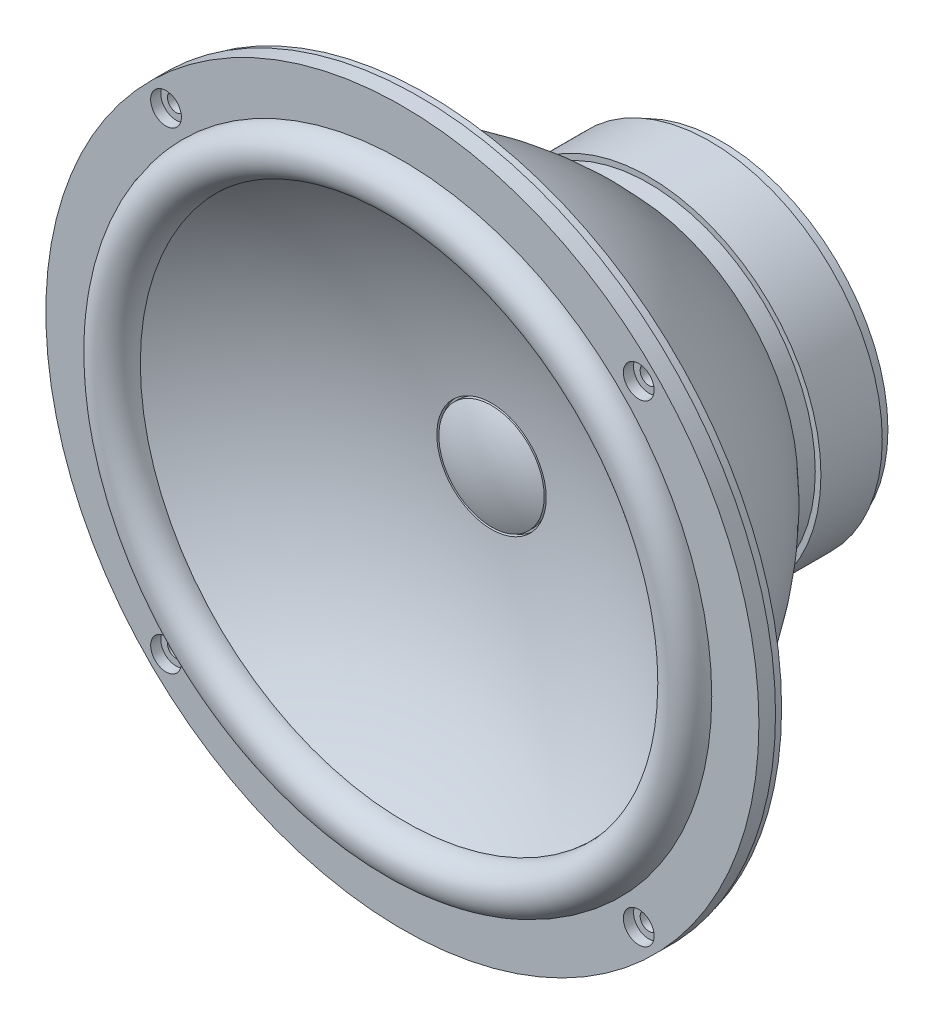
SolidWorks part; units mm, degrees
ref_plane "Front Plane" through (0, 0, 0) normal (0, 0, 1) x (1, 0, 0)
ref_plane "Top Plane" through (0, 0, 0) normal (0, 1, 0) x (1, 0, 0)
ref_plane "Right Plane" through (0, 0, 0) normal (1, 0, 0) x (0, 0, -1)
sketch "Sketch1" plane through (0, 0, 0) normal (0, 1, 0) x (1, 0, 0)
  line L0 (0, 0) -> (0, 85.8) construction
  line L1 (0, 0) -> (85.6836, 0) construction
  line L2 (13.5, 22) -> (13, 22) construction
  line L3 (76.3601, 0) -> (88, 0)
  line L4 (88, 0) -> (88, 4.1)
  line L5 (87.5, 6.1) -> (72.25, 6.1)
  line L6 (41.1071, 56.4856) -> (41.1071, 60.8036)
  line L7 (41.1071, 60.8036) -> (42.5, 60.8036)
  line L8 (42.5, 60.8036) -> (42.5, 75.942)
  line L9 (42.5, 75.942) -> (41.1071, 75.942)
  line L10 (41.1071, 75.942) -> (41.1071, 78.736)
  line L11 (17.526, 82.8) -> (5, 82.8)
  line L12 (0, 19.2404) -> (0, 85.8)
  line L13 (94.1144, -5.5) -> (59.7166, -5.5) construction
  line L14 (88, 4.1) -> (87.5, 4.1)
  line L15 (87.5, 4.1) -> (87.5, 6.1)
  line L16 (13.5, 22) -> (13.5, 23)
  line L17 (13.5, 23) -> (13, 23)
  line L18 (13, 23) -> (13, 22)
  line L19 (0, 19.2404) -> (-22.7747, 19.2404) construction
  line L20 (5, 82.8) -> (5, 83.8)
  line L21 (5, 83.8) -> (2, 83.8)
  line L22 (2, 83.8) -> (2, 85.8)
  line L23 (2, 85.8) -> (0, 85.8)
  line L24 (0, 85.8) -> (0, 91.3085) construction
  arc A1 (13.5, 22) -> (65.3427, 0.6614) centre (2.8851, -77.435) cw
  arc A2 (72.25, 6.1) -> (41.1071, 56.4856) centre (-25.992, -19.8052) ccw
  arc A3 (41.1071, 78.736) -> (17.526, 82.8) centre (17.526, 12.3542) ccw
  arc A4 (76.3601, 0) -> (65.3427, 0.6614) centre (70.8332, 0.027) cw
  arc A5 (13, 22) -> (0, 19.2404) centre (0, 51.2404) cw
  dimension "D1" = 176
  dimension "D14" = 26
  dimension "D16" = 101.6
  dimension "D4" = 88.3
  dimension "D19" = 32
  dimension "D20" = 100
  dimension "D2" = 76.7
  dimension "D3" = 35.052
  dimension "D5" = 15.1384
  dimension "D6" = 4.1
  dimension "D7" = 2
  dimension "D8" = 0.5
  dimension "D9" = 0.5
  dimension "D10" = 2.794
  dimension "D11" = 4.318
  dimension "D12" = 85
  dimension "D13" = 1
  dimension "D15" = 6.858
  dimension "D17" = 144.5
  dimension "D18" = 22
  dimension "D21" = 4
  dimension "D22" = 10
  dimension "D23" = 1
  dimension "D24" = 3
revolve "Revolve1" add sketch "Sketch1" angle 360 about L12
sketch "Sketch3" plane through (0, 0, 0) normal (0, 0, 1) x (1, 0, 0)
  line L0 (0, 0) -> (-58.3363, 58.3363) construction
  line L2 (0, 0) -> (0, 61.468) construction
  line L4 (0, 0) -> (58.3363, 58.3363) construction
  line L6 (0, 0) -> (58.3363, -58.3363) construction
  line L8 (0, 0) -> (-58.3363, -58.3363) construction
  circle A0 centre (-58.3363, 58.3363) radius 2.15
  circle A3 centre (58.3363, 58.3363) radius 2.15
  circle A5 centre (58.3363, -58.3363) radius 2.15
  circle A7 centre (-58.3363, -58.3363) radius 2.15
  point P3 (0, 0)
  point P4 (-62, 54.2172)
  point P6 (-57.6873, 56.476)
  point P7 (0, 0)
  point P12 (0, 0)
  point P13 (0, 0)
  point P16 (0, 0)
  point P23 (0, 0)
  point P26 (0, 0)
  point P28 (0, 0)
  point P29 (0, 0)
  point P30 (0, 0)
  point P31 (0, 0)
  dimension "D1" = 4.3
  dimension "D2" = 165
  dimension "D4" = 45
  dimension "D5" = 4
extrude "Cut holes" cut sketch "Sketch3" against normal through all
sketch "Sketch4" plane through (0, 0, 0) normal (0, 0, 1) x (1, 0, 0)
  circle A0 centre (-58.3363, 58.3363) radius 3.7973
  circle A2 centre (58.3363, 58.3363) radius 3.7973
  circle A4 centre (58.3363, -58.3363) radius 3.7973
  circle A6 centre (-58.3363, -58.3363) radius 3.7973
  point P3 (0, 0)
  point P4 (0, 0)
  point P9 (58.3363, 58.3363)
  point P10 (58.3363, -58.3363)
  point P24 (0, 0)
  dimension "D1" = 7.5946
extrude "Cut-Extrude4" cut sketch "Sketch4" against normal blind 2.5019
